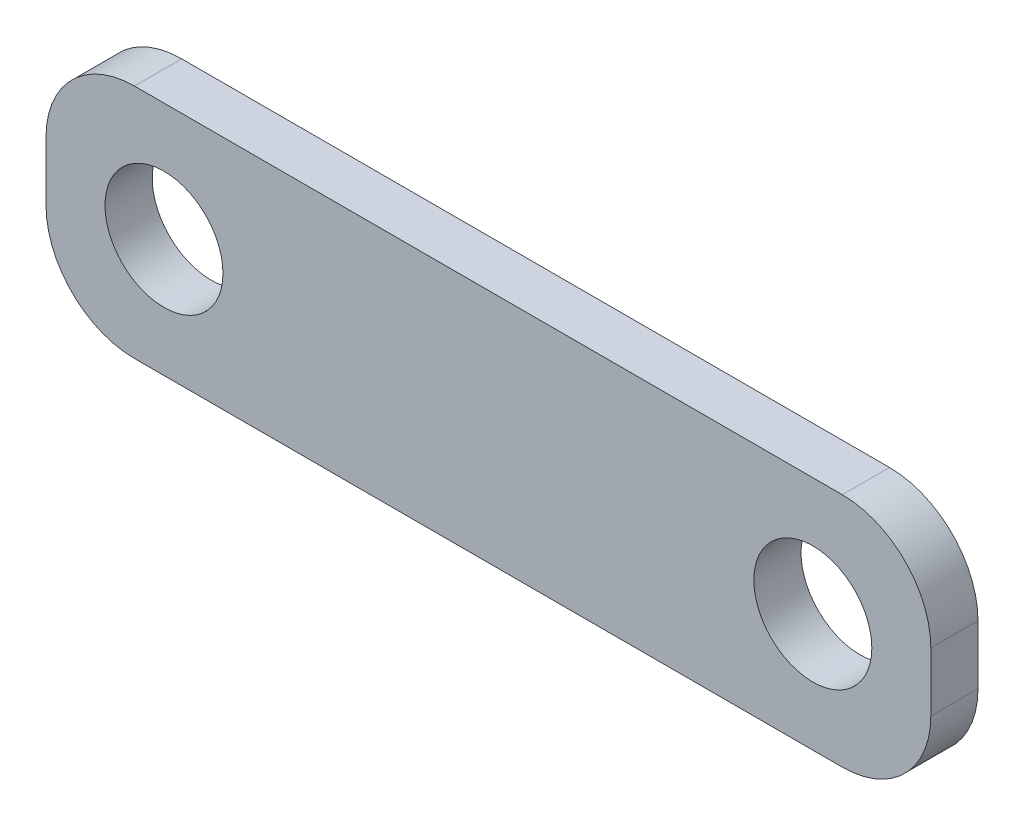
SolidWorks part; units mm, degrees
ref_plane "Plano frontal" through (0, 0, 0) normal (0, 0, 1) x (1, 0, 0)
ref_plane "Plano superior" through (0, 0, 0) normal (0, 1, 0) x (1, 0, 0)
ref_plane "Plano direito" through (0, 0, 0) normal (1, 0, 0) x (0, 0, -1)
sketch "Esboço1" plane through (0, 0, 0) normal (0, 0, 1) x (1, 0, 0)
  line L0 (0, 0) -> (0, 40)
  line L1 (0, 40) -> (150, 40)
  line L2 (150, 40) -> (150, 0)
  line L3 (150, 0) -> (0, 0)
  dimension "D1" = 40
  dimension "D2" = 150
extrude "Ressalto-extrusão1" add sketch "Esboço1" along normal mid plane 8
fillet "Filete2" radius 15 4 edges at (150, 0, 0) (150, 40, 0) (0, 0, 0) (0, 40, 0)
hole_wizard "Furos-guia com Ø20.0mm1" positions "Esboço7" profile "Esboço6" hole size "Ø20.0" standard "Ansi Metric" end condition through all
sketch "Esboço7" plane through (0, 0, 4) normal (0, 0, 1) x (1, 0, 0)
  line L0 (0, 25) -> (0, 15) construction
  line L1 (150, 15) -> (150, 25) construction
  line L2 (15, 0) -> (135, 0) construction
  point P2 (20, 20)
  point P9 (130, 20)
  dimension "D1" = 20
  dimension "D2" = 20
  dimension "D3" = 20
  dimension "D4" = 20
sketch "Esboço6" plane through (20, 20, 4) normal (1, 0, 0) x (0, -1, 0)
  line L0 (0, 0) -> (0, 8)
  line L1 (0, 8) -> (10, 8)
  line L2 (10, 8) -> (10, 0)
  line L5 (10, 0) -> (0, 0)
  line L11 (0, -6.35) -> (0, 107.95) construction
  dimension "Thru Hole Dia." = 20
  dimension "Thru Hole Depth" = 8
